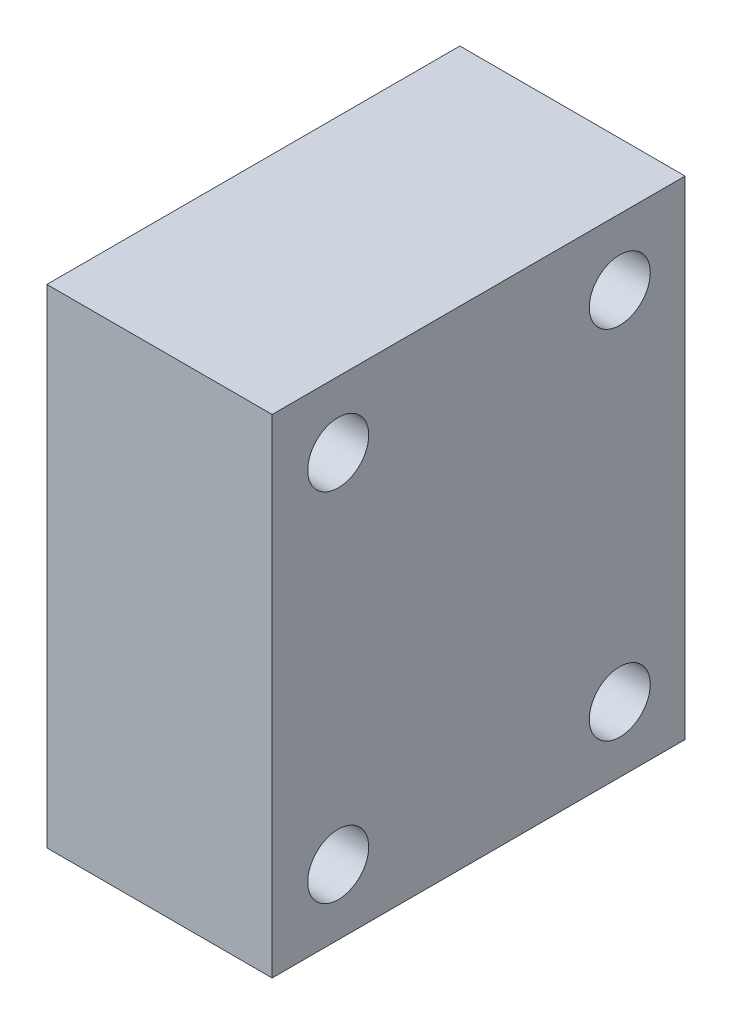
SolidWorks part; units mm, degrees
ref_plane "Front Plane" through (0, 0, 0) normal (1, 0, 0) x (0, 1, 0)
ref_plane "Top Plane" through (0, 0, 0) normal (0, 0, 1) x (0, 1, 0)
ref_plane "Right Plane" through (0, 0, 0) normal (0, 1, 0) x (-1, 0, 0)
sketch "Sketch1" plane through (0, 0, 0) normal (1, 0, 0) x (0, 1, 0)
  line L1 (0, 0) -> (82.55, 0)
  line L2 (0, 0) -> (0, 69.85)
  line L3 (0, 69.85) -> (82.55, 69.85)
  line L4 (82.55, 0) -> (82.55, 69.85)
extrude "Boss-Extrude1" add sketch "Sketch1" along normal blind 38.1
sketch "Sketch2" plane through (0, 0, 0) normal (1, 0, 0) x (0, 1, 0)
  circle A0 centre (11.049, 11.049) radius 5.1594
  circle A1 centre (71.374, 11.049) radius 5.1594
  circle A2 centre (11.049, 58.674) radius 5.1594
  circle A3 centre (71.374, 58.674) radius 5.1594
extrude "Cut-Extrude2" cut sketch "Sketch2" along normal through all
sketch "Sketch3" plane through (0, 0, 0) normal (1, 0, 0) x (0, 1, 0)
  circle A0 centre (23.622, 34.798) radius 7.3422
  circle A1 centre (58.674, 34.798) radius 7.3422
extrude "Cut-Extrude3" cut sketch "Sketch3" along normal blind 28.448
sketch "Sketch4" plane through (0, 0, 0) normal (1, 0, 0) x (0, 1, 0)
  circle A0 centre (23.622, 34.798) radius 12.7254
  circle A1 centre (58.674, 34.798) radius 12.7254
extrude "Cut-Extrude4" cut sketch "Sketch4" along normal blind 2.8194
